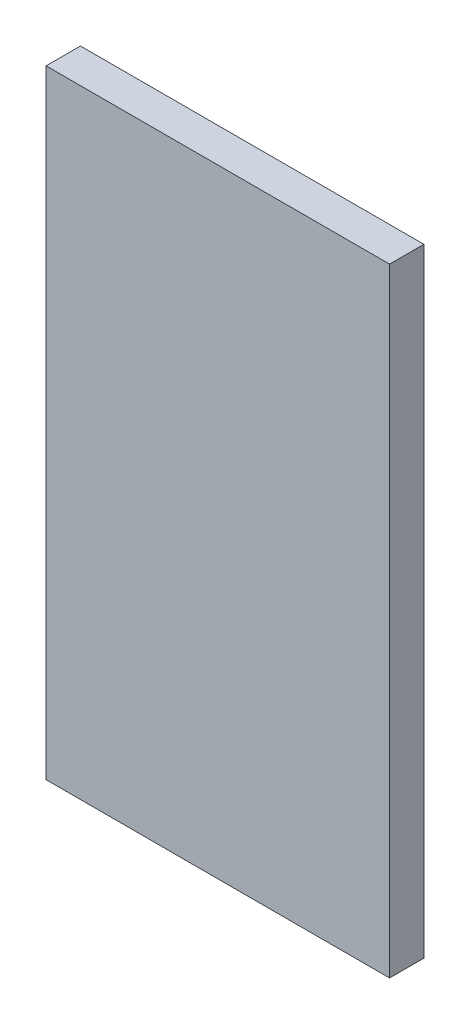
SolidWorks part; units mm, degrees
ref_plane "Plan de face" through (0, 0, 0) normal (0, 0, 1) x (1, 0, 0)
ref_plane "Plan de dessus" through (0, 0, 0) normal (0, 1, 0) x (1, 0, 0)
ref_plane "Plan de droite" through (0, 0, 0) normal (1, 0, 0) x (0, 0, -1)
sketch "Esquisse1" plane through (0, 0, 0) normal (0, 0, 1) x (1, 0, 0)
  line L0 (0, 0) -> (0, 180)
  line L1 (0, 180) -> (100, 180)
  line L2 (100, 180) -> (100, 0)
  line L3 (100, 0) -> (0, 0)
  dimension "D1" = 180
  dimension "D2" = 100
extrude "Boss.-Extru.1" add sketch "Esquisse1" along normal blind 10
